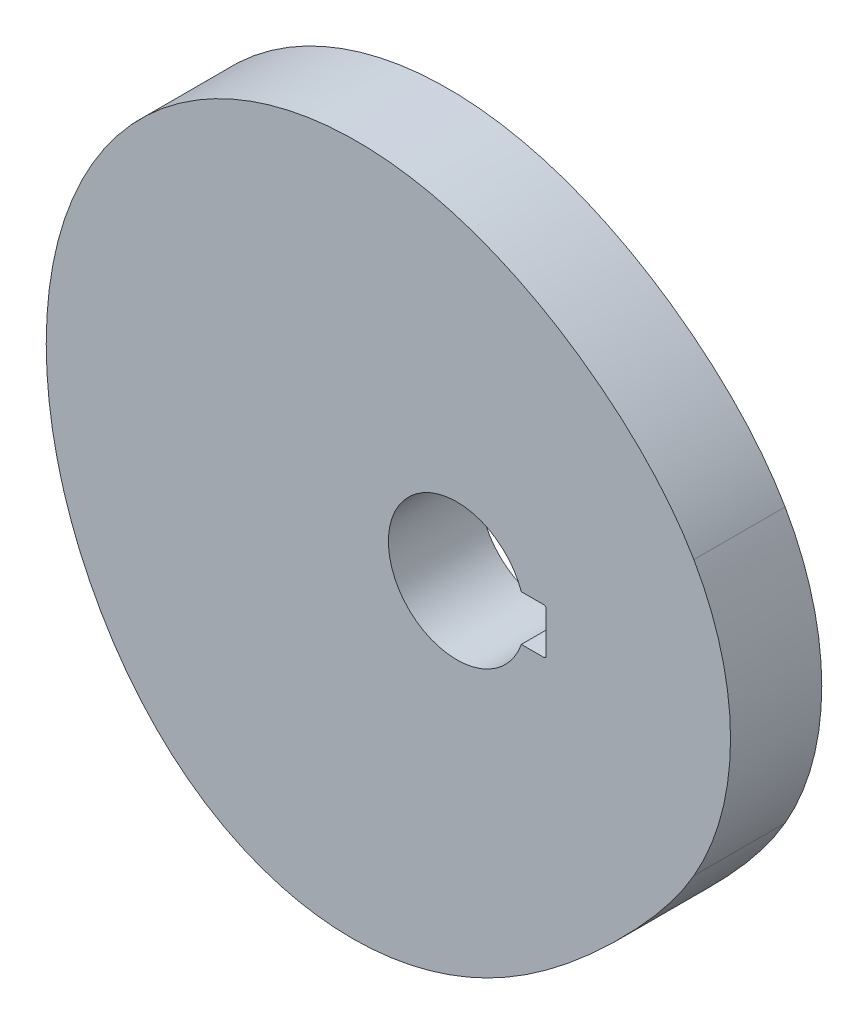
SolidWorks part; units mm, degrees
material "Plain Carbon Steel"
ref_plane "Front Plane" through (0, 0, 0) normal (0, 0, 1) x (1, 0, 0)
ref_plane "Top Plane" through (0, 0, 0) normal (0, 1, 0) x (1, 0, 0)
ref_plane "Right Plane" through (0, 0, 0) normal (1, 0, 0) x (0, 0, -1)
sketch "Displacement Sketch" plane through (0, 0, 0) normal (0, 0, 1) x (1, 0, 0)
  line L0 (0, 15) -> (0, 0) construction
  line L1 (0, 0) -> (47.1239, 0) construction
  line L2 (3.927, 0) -> (3.927, 15) construction
  line L3 (23.5619, 0) -> (23.5619, 15) construction
  line L4 (27.4889, 0) -> (27.4889, 15) construction
  line L5 (43.1969, 0) -> (43.1969, 15) construction
  line L6 (47.1239, 0) -> (47.1239, 15) construction
  line L7 (0, 0) -> (3.927, 0)
  line L8 (27.4889, 15) -> (23.5619, 15)
  line L9 (43.1969, 0) -> (47.1239, 0)
  spline S0 degree 4 poles (1.962, -0.0967) (2.0251, -0.0879) (2.1497, -0.0715) (2.3802, -0.0441) (2.7786, -0.0172) (3.1491, -0.0023) (3.8234, 0.0011) (4.1519, -0.0013) (4.7825, 0.0037) (5.2973, 0.0292) (5.8993, 0.0828) (6.4992, 0.198) (7.1843, 0.4092) (7.8229, 0.6945) (8.5028, 1.0958) (9.2434, 1.664) (10.1514, 2.5325) (11.1276, 3.6845) (12.1583, 5.0983) (13.2223, 6.6951) (14.2666, 8.3049) (15.3308, 9.9017) (16.361, 11.3155) (17.3382, 12.4675) (18.2447, 13.336) (18.9876, 13.9042) (19.6636, 14.3055) (20.2354, 14.5584) (20.6913, 14.7109) (21.0546, 14.8041) (21.3223, 14.8591) (21.5625, 14.8998) (21.7937, 14.9296) (22.0274, 14.9566) (22.3642, 14.9781) (22.6856, 14.9963) (23.3417, 15.0013) (23.6628, 14.9989) (24.3418, 15.0023) (24.7635, 15.0193) (25.1747, 15.049) (25.3985, 15.0791) (25.5259, 15.0967) knots 0 0 0 0 0 0.008159 0.016318 0.032637 0.048955 0.065274 0.0892 0.101163 0.113126 0.142767 0.163984 0.185201 0.206418 0.236195 0.268021 0.309045 0.372696 0.436348 0.5 0.563652 0.627304 0.690955 0.731979 0.763805 0.793582 0.814799 0.836016 0.846625 0.857233 0.864643 0.872053 0.879463 0.886874 0.898837 0.9108 0.934726 0.951045 0.967363 0.983682 1 1 1 1 1 construction
  spline S1 degree 4 poles (3.927, 0) (4.0838, 0) (4.3123, 0) (4.7825, 0.0037) (5.2973, 0.0292) (5.8993, 0.0828) (6.4992, 0.198) (7.1843, 0.4092) (7.8229, 0.6945) (8.5028, 1.0958) (9.2434, 1.664) (10.1514, 2.5325) (11.1276, 3.6845) (12.1583, 5.0983) (13.2223, 6.6951) (14.2666, 8.3049) (15.3308, 9.9017) (16.361, 11.3155) (17.3382, 12.4675) (18.2447, 13.336) (18.9876, 13.9042) (19.6636, 14.3055) (20.2354, 14.5584) (20.6913, 14.7109) (21.0546, 14.8041) (21.3223, 14.8591) (21.5625, 14.8998) (21.7937, 14.9296) (22.0274, 14.9566) (22.3642, 14.9781) (22.6856, 14.9963) (23.1748, 15) (23.4052, 15) (23.5619, 15) knots 0.065274 0.065274 0.065274 0.065274 0.065274 0.0892 0.101163 0.113126 0.142767 0.163984 0.185201 0.206418 0.236195 0.268021 0.309045 0.372696 0.436348 0.5 0.563652 0.627304 0.690955 0.731979 0.763805 0.793582 0.814799 0.836016 0.846625 0.857233 0.864643 0.872053 0.879463 0.886874 0.898837 0.9108 0.934726 0.934726 0.934726 0.934726 0.934726
  spline S2 degree 4 poles (25.917, 15.0967) (25.9672, 15.0879) (26.0664, 15.0716) (26.2503, 15.0442) (26.5692, 15.0173) (26.8684, 15.0023) (27.398, 14.9989) (27.6696, 15.0012) (28.1638, 14.9965) (28.4688, 14.9775) (28.7956, 14.949) (29.0691, 14.9044) (29.3652, 14.8416) (29.6303, 14.7623) (29.8895, 14.6683) (30.1363, 14.5572) (30.3781, 14.4298) (30.708, 14.2278) (31.1287, 13.9151) (31.7056, 13.3799) (32.4321, 12.5171) (33.1948, 11.3999) (33.9837, 10.0588) (34.759, 8.6207) (35.5133, 7.1717) (36.2737, 5.7258) (37.0683, 4.2981) (37.8437, 3.0586) (38.5964, 2.0494) (39.2866, 1.3197) (39.8479, 0.8516) (40.4053, 0.501) (40.8925, 0.2823) (41.3433, 0.149) (41.8164, 0.0573) (42.2412, 0.0166) (42.6103, 0.0017) (43.0977, -0.0005) (43.3551, 0.0006) (43.8251, -0.0023) (44.1115, -0.0173) (44.4386, -0.0442) (44.6184, -0.0716) (44.7185, -0.0879) (44.7693, -0.0967) knots 0 0 0 0 0 0.007472 0.014944 0.029888 0.044832 0.059777 0.081272 0.09202 0.102768 0.114604 0.126441 0.136767 0.147094 0.15742 0.167746 0.178072 0.188398 0.21612 0.247099 0.297177 0.359134 0.421092 0.48305 0.545008 0.606966 0.668924 0.730882 0.766656 0.797635 0.820922 0.841574 0.866069 0.878735 0.891402 0.915813 0.928018 0.940223 0.955168 0.970112 0.985056 0.992528 1 1 1 1 1 construction
  spline S3 degree 4 poles (27.4889, 15) (27.6137, 15) (27.7971, 15) (28.1638, 14.9965) (28.4688, 14.9775) (28.7956, 14.949) (29.0691, 14.9044) (29.3652, 14.8416) (29.6303, 14.7623) (29.8895, 14.6683) (30.1363, 14.5572) (30.3781, 14.4298) (30.708, 14.2278) (31.1287, 13.9151) (31.7056, 13.3799) (32.4321, 12.5171) (33.1948, 11.3999) (33.9837, 10.0588) (34.759, 8.6207) (35.5133, 7.1717) (36.2737, 5.7258) (37.0683, 4.2981) (37.8437, 3.0586) (38.5964, 2.0494) (39.2866, 1.3197) (39.8479, 0.8516) (40.4053, 0.501) (40.8925, 0.2823) (41.3433, 0.149) (41.8164, 0.0573) (42.2412, 0.0166) (42.6103, 0.0017) (42.9834, 0) (43.1261, 0) (43.1969, 0) knots 0.059777 0.059777 0.059777 0.059777 0.059777 0.081272 0.09202 0.102768 0.114604 0.126441 0.136767 0.147094 0.15742 0.167746 0.178072 0.188398 0.21612 0.247099 0.297177 0.359134 0.421092 0.48305 0.545008 0.606966 0.668924 0.730882 0.766656 0.797635 0.820922 0.841574 0.866069 0.878735 0.891402 0.915813 0.928018 0.940223 0.940223 0.940223 0.940223 0.940223
  point P2 (0, 0)
  point P17 (0, 0)
  dimension "D1" = 15
  dimension "D2" = 47.1239
  dimension "D3" = 3.927
  dimension "D4" = 19.635
  dimension "D5" = 3.927
  dimension "D6" = 15.708
  dimension "D7" = 3.927
sketch "Velocity Sketch" plane through (0, 0, 0) normal (0, 0, 1) x (1, 0, 0)
  line L0 (0, -15) -> (0, -65) construction
  line L1 (0, -40) -> (47.1239, -40) construction
  line L2 (3.927, -15) -> (3.927, -65) construction
  line L3 (23.5619, -15) -> (23.5619, -65) construction
  line L4 (27.4889, -15) -> (27.4889, -65) construction
  line L5 (43.1969, -15) -> (43.1969, -65) construction
  line L6 (47.1239, -15) -> (47.1239, -65) construction
  line L7 (0, -40) -> (3.927, -40)
  line L8 (23.5619, -40) -> (27.4889, -40)
  line L9 (43.1969, -40) -> (47.1239, -40)
  spline S0 degree 4 poles (1.9635, -38.9057) (2.0257, -38.9728) (2.1526, -39.1046) (2.3179, -39.263) (2.5282, -39.4396) (2.7124, -39.5752) (2.8656, -39.6755) (3.0312, -39.7696) (3.21, -39.8541) (3.378, -39.9155) (3.5323, -39.9566) (3.6606, -39.9808) (3.7704, -39.9939) (3.8976, -40.0012) (3.9765, -40.0003) (4.0914, -39.9931) (4.2047, -39.9788) (4.3113, -39.9585) (4.4273, -39.9287) (4.5497, -39.8882) (4.6855, -39.8341) (4.8338, -39.7637) (5.0005, -39.6692) (5.2228, -39.5203) (5.4703, -39.3234) (5.7369, -39.0742) (6.0182, -38.7713) (6.2635, -38.4767) (6.4789, -38.1966) (6.7119, -37.8755) (6.9601, -37.5119) (7.2378, -37.08) (7.6188, -36.4531) (8.0578, -35.69) (8.695, -34.5334) (9.3923, -33.2428) (10.1106, -31.9631) (10.8521, -30.798) (11.4447, -29.9912) (12.0701, -29.306) (12.6823, -28.8165) (13.3594, -28.5265) (13.9982, -28.5224) (14.4931, -28.6816) (14.9938, -28.9673) (15.4821, -29.3759) (16.0352, -29.9801) (16.6301, -30.7877) (17.3726, -31.9534) (18.0917, -33.2337) (18.7893, -34.5249) (19.4267, -35.6821) (19.8657, -36.4456) (20.2468, -37.073) (20.5641, -37.567) (20.8732, -38.0148) (21.1744, -38.4151) (21.4671, -38.7672) (21.7491, -39.0713) (22.0564, -39.3589) (22.3514, -39.5861) (22.6045, -39.7396) (22.8026, -39.8338) (22.9386, -39.888) (23.0611, -39.9286) (23.1771, -39.9584) (23.2842, -39.9788) (23.3789, -39.9907) (23.4581, -39.9971) (23.5401, -40.0006) (23.6106, -40) (23.7191, -39.9939) (23.8283, -39.9808) (23.9566, -39.9566) (24.111, -39.9155) (24.322, -39.8383) (24.5805, -39.7075) (24.8544, -39.5266) (25.138, -39.2946) (25.3363, -39.1046) (25.4632, -38.9728) (25.5254, -38.9057) knots 0 0 0 0 0 0.010194 0.020387 0.025484 0.030581 0.035677 0.040774 0.046689 0.052603 0.05556 0.058517 0.061474 0.064432 0.068544 0.0706 0.072656 0.076768 0.08088 0.083926 0.086973 0.093066 0.099159 0.105252 0.116762 0.128271 0.13978 0.15129 0.159464 0.167638 0.183987 0.200336 0.216684 0.249382 0.282079 0.347474 0.380171 0.412868 0.435887 0.458906 0.483278 0.499726 0.516191 0.528398 0.540605 0.563699 0.586794 0.619507 0.652221 0.717647 0.750361 0.783074 0.799431 0.815787 0.832144 0.8485 0.860048 0.871595 0.883143 0.89469 0.906897 0.913 0.916052 0.919104 0.92322 0.927336 0.929394 0.931452 0.93351 0.935568 0.938526 0.941483 0.94444 0.947397 0.953311 0.959226 0.969419 0.979613 0.989806 1 1 1 1 1 construction
  spline S1 degree 4 poles (3.927, -40) (3.9591, -40) (4.0069, -39.9984) (4.0914, -39.9931) (4.2047, -39.9788) (4.3113, -39.9585) (4.4273, -39.9287) (4.5497, -39.8882) (4.6855, -39.8341) (4.8338, -39.7637) (5.0005, -39.6692) (5.2228, -39.5203) (5.4703, -39.3234) (5.7369, -39.0742) (6.0182, -38.7713) (6.2635, -38.4767) (6.4789, -38.1966) (6.7119, -37.8755) (6.9601, -37.5119) (7.2378, -37.08) (7.6188, -36.4531) (8.0578, -35.69) (8.695, -34.5334) (9.3923, -33.2428) (10.1106, -31.9631) (10.8521, -30.798) (11.4447, -29.9912) (12.0701, -29.306) (12.6823, -28.8165) (13.3594, -28.5265) (13.9982, -28.5224) (14.4931, -28.6816) (14.9938, -28.9673) (15.4821, -29.3759) (16.0352, -29.9801) (16.6301, -30.7877) (17.3726, -31.9534) (18.0917, -33.2337) (18.7893, -34.5249) (19.4267, -35.6821) (19.8657, -36.4456) (20.2468, -37.073) (20.5641, -37.567) (20.8732, -38.0148) (21.1744, -38.4151) (21.4671, -38.7672) (21.7491, -39.0713) (22.0564, -39.3589) (22.3514, -39.5861) (22.6045, -39.7396) (22.8026, -39.8338) (22.9386, -39.888) (23.0611, -39.9286) (23.1771, -39.9584) (23.2842, -39.9788) (23.3789, -39.9907) (23.4581, -39.9971) (23.5136, -39.9995) (23.5459, -40) (23.5619, -40) knots 0.064432 0.064432 0.064432 0.064432 0.064432 0.068544 0.0706 0.072656 0.076768 0.08088 0.083926 0.086973 0.093066 0.099159 0.105252 0.116762 0.128271 0.13978 0.15129 0.159464 0.167638 0.183987 0.200336 0.216684 0.249382 0.282079 0.347474 0.380171 0.412868 0.435887 0.458906 0.483278 0.499726 0.516191 0.528398 0.540605 0.563699 0.586794 0.619507 0.652221 0.717647 0.750361 0.783074 0.799431 0.815787 0.832144 0.8485 0.860048 0.871595 0.883143 0.89469 0.906897 0.913 0.916052 0.919104 0.92322 0.927336 0.929394 0.931452 0.93351 0.935568 0.935568 0.935568 0.935568 0.935568
  spline S2 degree 4 poles (25.9181, -41.3678) (25.969, -41.2822) (26.0474, -41.155) (26.1567, -40.9884) (26.3034, -40.7872) (26.428, -40.6317) (26.5612, -40.4834) (26.7044, -40.3447) (26.8491, -40.2282) (26.9938, -40.1353) (27.1202, -40.0746) (27.2225, -40.0387) (27.3087, -40.0172) (27.3821, -40.0055) (27.4558, -39.9999) (27.5062, -39.9994) (27.5651, -40.003) (27.6216, -40.0095) (27.6752, -40.0191) (27.7266, -40.0316) (27.79, -40.0509) (27.8853, -40.0869) (28.0075, -40.1485) (28.1907, -40.2707) (28.3839, -40.4445) (28.5692, -40.6505) (28.7482, -40.8845) (28.8972, -41.1024) (29.0371, -41.3263) (29.1693, -41.5547) (29.3267, -41.8447) (29.5183, -42.2252) (29.738, -42.6988) (29.9816, -43.2668) (30.2236, -43.8681) (30.5135, -44.6245) (30.8469, -45.5378) (31.2234, -46.6076) (31.6487, -47.832) (32.0801, -49.0542) (32.4735, -50.118) (32.8326, -51.0215) (33.142, -51.7326) (33.3888, -52.2556) (33.6408, -52.7378) (33.8982, -53.1762) (34.223, -53.6432) (34.5556, -54.0066) (34.9078, -54.2495) (35.2458, -54.3293) (35.458, -54.327) (35.7081, -54.2632) (35.9731, -54.1157) (36.2611, -53.8668) (36.5554, -53.5158) (36.8301, -53.1086) (37.0915, -52.6536) (37.3438, -52.1599) (37.5898, -51.63) (37.8954, -50.918) (38.2495, -50.0196) (38.6386, -48.9625) (39.0662, -47.7483) (39.4887, -46.5322) (39.8632, -45.4699) (40.1952, -44.5632) (40.4842, -43.8123) (40.7255, -43.2156) (40.9683, -42.653) (41.187, -42.1848) (41.3776, -41.8095) (41.5335, -41.5246) (41.6646, -41.3002) (41.8032, -41.0803) (41.9509, -40.8664) (42.1281, -40.6369) (42.3115, -40.4352) (42.5023, -40.2652) (42.6833, -40.1457) (42.8038, -40.0854) (42.8984, -40.0501) (42.9739, -40.0273) (43.0476, -40.0102) (43.1489, -40) (43.2166, -39.9988) (43.3032, -40.0055) (43.3772, -40.0172) (43.4633, -40.0387) (43.5656, -40.0746) (43.6921, -40.1353) (43.8367, -40.2282) (43.9814, -40.3447) (44.1247, -40.4834) (44.2578, -40.6317) (44.3824, -40.7872) (44.5292, -40.9884) (44.6384, -41.155) (44.7169, -41.2822) (44.7677, -41.3678) knots 0 0 0 0 0 0.010463 0.015694 0.020925 0.026157 0.031388 0.03662 0.041851 0.045635 0.049419 0.051311 0.053203 0.055095 0.056987 0.058388 0.05979 0.061191 0.062592 0.063993 0.065395 0.068197 0.073266 0.078335 0.088472 0.095404 0.102336 0.109267 0.116199 0.123131 0.130063 0.143926 0.160948 0.17797 0.194992 0.212014 0.246057 0.280101 0.314145 0.348188 0.382232 0.399254 0.416276 0.429638 0.443 0.456362 0.469724 0.489196 0.494701 0.500206 0.505766 0.511326 0.521544 0.531762 0.545538 0.559313 0.573088 0.586864 0.60377 0.620676 0.654487 0.688299 0.722111 0.755922 0.789734 0.80664 0.823546 0.840451 0.857357 0.871007 0.877832 0.884657 0.891482 0.898307 0.905132 0.911957 0.921925 0.926909 0.931893 0.934673 0.936063 0.937453 0.940233 0.943013 0.944905 0.946797 0.948689 0.950581 0.954365 0.958149 0.96338 0.968612 0.973843 0.979075 0.984306 0.989537 1 1 1 1 1 construction
  spline S3 degree 4 poles (27.4889, -40) (27.5008, -40) (27.5245, -40.0005) (27.5651, -40.003) (27.6216, -40.0095) (27.6752, -40.0191) (27.7266, -40.0316) (27.79, -40.0509) (27.8853, -40.0869) (28.0075, -40.1485) (28.1907, -40.2707) (28.3839, -40.4445) (28.5692, -40.6505) (28.7482, -40.8845) (28.8972, -41.1024) (29.0371, -41.3263) (29.1693, -41.5547) (29.3267, -41.8447) (29.5183, -42.2252) (29.738, -42.6988) (29.9816, -43.2668) (30.2236, -43.8681) (30.5135, -44.6245) (30.8469, -45.5378) (31.2234, -46.6076) (31.6487, -47.832) (32.0801, -49.0542) (32.4735, -50.118) (32.8326, -51.0215) (33.142, -51.7326) (33.3888, -52.2556) (33.6408, -52.7378) (33.8982, -53.1762) (34.223, -53.6432) (34.5556, -54.0066) (34.9078, -54.2495) (35.2458, -54.3293) (35.458, -54.327) (35.7081, -54.2632) (35.9731, -54.1157) (36.2611, -53.8668) (36.5554, -53.5158) (36.8301, -53.1086) (37.0915, -52.6536) (37.3438, -52.1599) (37.5898, -51.63) (37.8954, -50.918) (38.2495, -50.0196) (38.6386, -48.9625) (39.0662, -47.7483) (39.4887, -46.5322) (39.8632, -45.4699) (40.1952, -44.5632) (40.4842, -43.8123) (40.7255, -43.2156) (40.9683, -42.653) (41.187, -42.1848) (41.3776, -41.8095) (41.5335, -41.5246) (41.6646, -41.3002) (41.8032, -41.0803) (41.9509, -40.8664) (42.1281, -40.6369) (42.3115, -40.4352) (42.5023, -40.2652) (42.6833, -40.1457) (42.8038, -40.0854) (42.8984, -40.0501) (42.9739, -40.0273) (43.0476, -40.0102) (43.1272, -40.0021) (43.1735, -40) (43.1969, -40) knots 0.056987 0.056987 0.056987 0.056987 0.056987 0.058388 0.05979 0.061191 0.062592 0.063993 0.065395 0.068197 0.073266 0.078335 0.088472 0.095404 0.102336 0.109267 0.116199 0.123131 0.130063 0.143926 0.160948 0.17797 0.194992 0.212014 0.246057 0.280101 0.314145 0.348188 0.382232 0.399254 0.416276 0.429638 0.443 0.456362 0.469724 0.489196 0.494701 0.500206 0.505766 0.511326 0.521544 0.531762 0.545538 0.559313 0.573088 0.586864 0.60377 0.620676 0.654487 0.688299 0.722111 0.755922 0.789734 0.80664 0.823546 0.840451 0.857357 0.871007 0.877832 0.884657 0.891482 0.898307 0.905132 0.911957 0.921925 0.926909 0.931893 0.934673 0.936063 0.937453 0.940233 0.943013 0.943013 0.943013 0.943013 0.943013
  point P15 (23.5619, -40)
  point P27 (43.1969, -40)
  point P28 (3.927, -40)
  point P35 (27.4889, -40)
  dimension "D1" = 50
  dimension "D2" = 15
  dimension "D3" = 47.1239
sketch "Acceleration Sketch" plane through (0, 0, 0) normal (0, 0, 1) x (1, 0, 0)
  line L0 (0, -80) -> (0, -130) construction
  line L1 (0, -15) -> (0, -65) construction
  line L2 (3.927, -80) -> (3.927, -130) construction
  line L3 (23.5619, -80) -> (23.5619, -130) construction
  line L4 (27.4889, -80) -> (27.4889, -130) construction
  line L5 (43.1969, -80) -> (43.1969, -130) construction
  line L6 (47.1239, -80) -> (47.1239, -130) construction
  line L7 (0, -105) -> (47.1239, -105) construction
  spline S0 degree 4 poles (2.572, -110.7775) (2.5826, -110.7352) (2.6049, -110.6462) (2.6568, -110.4348) (2.7247, -110.1667) (2.8631, -109.5866) (2.9168, -109.376) (3.1103, -108.5487) (3.2451, -107.9915) (3.7647, -105.7173) (3.9235, -105.0128) (4.4418, -102.7383) (4.726, -101.5165) (5.0905, -99.9824) (5.4257, -98.6411) (5.7628, -97.3573) (6.0541, -96.3347) (6.324, -95.4451) (6.5477, -94.7627) (6.7807, -94.1024) (7.0182, -93.4965) (7.2387, -92.994) (7.4321, -92.6044) (7.6103, -92.2868) (7.7652, -92.0405) (7.9385, -91.8029) (8.1364, -91.5783) (8.3751, -91.3792) (8.6628, -91.239) (9.0399, -91.2355) (9.3821, -91.4294) (9.658, -91.7026) (9.9031, -92.031) (10.1006, -92.3508) (10.3757, -92.8619) (10.6941, -93.5774) (11.0415, -94.5007) (11.4096, -95.6315) (11.7539, -96.8019) (12.0819, -98.0088) (12.4807, -99.5681) (12.9408, -101.482) (13.4552, -103.72) (14.0337, -106.28) (14.5481, -108.518) (15.0082, -110.4319) (15.4071, -111.9912) (15.735, -113.1981) (16.0793, -114.3685) (16.4474, -115.4993) (16.7948, -116.4226) (17.1133, -117.1381) (17.3883, -117.6492) (17.5858, -117.969) (17.831, -118.2974) (18.1068, -118.5706) (18.449, -118.7645) (18.8261, -118.761) (19.1138, -118.6208) (19.3525, -118.4218) (19.5505, -118.197) (19.7664, -117.9009) (19.991, -117.5251) (20.221, -117.0728) (20.4706, -116.5036) (20.7083, -115.8976) (20.9412, -115.2374) (21.1649, -114.5549) (21.4349, -113.6653) (21.7261, -112.6427) (22.0633, -111.3589) (22.3985, -110.0176) (22.763, -108.4835) (23.0471, -107.2617) (23.5654, -104.9872) (23.7242, -104.2827) (24.2438, -102.0085) (24.3787, -101.4513) (24.5722, -100.624) (24.6258, -100.4134) (24.7642, -99.8333) (24.8321, -99.5652) (24.884, -99.3538) (24.9063, -99.2648) (24.917, -99.2225) knots 0 0 0 0 0 0.002588 0.005177 0.010354 0.020707 0.025884 0.031061 0.041414 0.082829 0.103192 0.123556 0.14392 0.164284 0.184648 0.205012 0.215194 0.225376 0.235558 0.24574 0.253858 0.261975 0.266034 0.270093 0.274152 0.278211 0.282468 0.286725 0.291483 0.295696 0.302677 0.307932 0.313188 0.318443 0.323699 0.340297 0.356895 0.373493 0.390091 0.408409 0.426727 0.463364 0.5 0.536636 0.573273 0.591591 0.609909 0.626507 0.643105 0.659703 0.676301 0.681557 0.686812 0.692068 0.697323 0.704304 0.708517 0.713275 0.717532 0.721789 0.725848 0.729907 0.738025 0.746142 0.75426 0.764442 0.774624 0.784806 0.794988 0.815352 0.835716 0.85608 0.876444 0.896808 0.917171 0.958586 0.968939 0.974116 0.979293 0.989646 0.994823 0.997412 1 1 1 1 1 construction
  spline S1 degree 4 poles (3.927, -105) (3.9944, -104.7033) (4.1329, -104.0938) (4.4418, -102.7383) (4.726, -101.5165) (5.0905, -99.9824) (5.4257, -98.6411) (5.7628, -97.3573) (6.0541, -96.3347) (6.324, -95.4451) (6.5477, -94.7627) (6.7807, -94.1024) (7.0182, -93.4965) (7.2387, -92.994) (7.4321, -92.6044) (7.6103, -92.2868) (7.7652, -92.0405) (7.9385, -91.8029) (8.1364, -91.5783) (8.3751, -91.3792) (8.6628, -91.239) (9.0399, -91.2355) (9.3821, -91.4294) (9.658, -91.7026) (9.9031, -92.031) (10.1006, -92.3508) (10.3757, -92.8619) (10.6941, -93.5774) (11.0415, -94.5007) (11.4096, -95.6315) (11.7539, -96.8019) (12.0819, -98.0088) (12.4807, -99.5681) (12.9408, -101.482) (13.4552, -103.72) (14.0337, -106.28) (14.5481, -108.518) (15.0082, -110.4319) (15.4071, -111.9912) (15.735, -113.1981) (16.0793, -114.3685) (16.4474, -115.4993) (16.7948, -116.4226) (17.1133, -117.1381) (17.3883, -117.6492) (17.5858, -117.969) (17.831, -118.2974) (18.1068, -118.5706) (18.449, -118.7645) (18.8261, -118.761) (19.1138, -118.6208) (19.3525, -118.4218) (19.5505, -118.197) (19.7664, -117.9009) (19.991, -117.5251) (20.221, -117.0728) (20.4706, -116.5036) (20.7083, -115.8976) (20.9412, -115.2374) (21.1649, -114.5549) (21.4349, -113.6653) (21.7261, -112.6427) (22.0633, -111.3589) (22.3985, -110.0176) (22.763, -108.4835) (23.0471, -107.2617) (23.356, -105.9062) (23.4945, -105.2967) (23.5619, -105) knots 0.082829 0.082829 0.082829 0.082829 0.082829 0.103192 0.123556 0.14392 0.164284 0.184648 0.205012 0.215194 0.225376 0.235558 0.24574 0.253858 0.261975 0.266034 0.270093 0.274152 0.278211 0.282468 0.286725 0.291483 0.295696 0.302677 0.307932 0.313188 0.318443 0.323699 0.340297 0.356895 0.373493 0.390091 0.408409 0.426727 0.463364 0.5 0.536636 0.573273 0.591591 0.609909 0.626507 0.643105 0.659703 0.676301 0.681557 0.686812 0.692068 0.697323 0.704304 0.708517 0.713275 0.717532 0.721789 0.725848 0.729907 0.738025 0.746142 0.75426 0.764442 0.774624 0.784806 0.794988 0.815352 0.835716 0.85608 0.876444 0.896808 0.917171 0.917171 0.917171 0.917171 0.917171
  spline S2 degree 4 poles (26.4484, -96.3102) (26.5118, -96.8222) (26.5658, -97.2281) (26.8032, -99.1812) (26.9742, -100.5869) (27.3892, -104.1392) (27.5686, -105.6882) (27.9878, -109.2775) (28.2426, -111.3928) (28.6075, -114.3425) (28.9332, -116.7713) (29.3318, -119.5372) (29.6889, -121.6296) (30.0509, -123.449) (30.3524, -124.5941) (30.5472, -125.2296) (30.7103, -125.6432) (30.821, -125.8896) (30.926, -126.0792) (31.0123, -126.2131) (31.0985, -126.3183) (31.1798, -126.3936) (31.2441, -126.4375) (31.2991, -126.4643) (31.3487, -126.4798) (31.3966, -126.4868) (31.4431, -126.4862) (31.491, -126.4779) (31.541, -126.4609) (31.5967, -126.4322) (31.6626, -126.3849) (31.7478, -126.3032) (31.8681, -126.1482) (32.0585, -125.8141) (32.3727, -125.0186) (32.7489, -123.6119) (33.1471, -121.6395) (33.5462, -119.2173) (33.9186, -116.6385) (34.2594, -114.0551) (34.5809, -111.4694) (34.8901, -108.8821) (35.1927, -106.2941) (35.4931, -103.7059) (35.7957, -101.1179) (36.1049, -98.5306) (36.4264, -95.9449) (36.7673, -93.3615) (37.1397, -90.7827) (37.5387, -88.3605) (37.9369, -86.3881) (38.3131, -84.9814) (38.6274, -84.1859) (38.8178, -83.8518) (38.9381, -83.6968) (39.0232, -83.6151) (39.0891, -83.5678) (39.1448, -83.5391) (39.1948, -83.5221) (39.2428, -83.5138) (39.2893, -83.5132) (39.3371, -83.5202) (39.3867, -83.5357) (39.4417, -83.5624) (39.506, -83.6068) (39.5872, -83.6808) (39.7, -83.8211) (39.8275, -84.031) (39.9606, -84.3179) (40.1387, -84.7711) (40.3334, -85.4056) (40.635, -86.5512) (40.9969, -88.3703) (41.354, -90.4629) (41.7526, -93.2287) (42.0783, -95.6575) (42.4432, -98.6072) (42.6981, -100.7225) (43.1172, -104.3118) (43.2966, -105.8608) (43.7116, -109.4131) (43.8826, -110.8188) (44.12, -112.7719) (44.174, -113.1778) (44.2375, -113.6898) knots 0 0 0 0 0 0.013744 0.027488 0.054976 0.082464 0.107561 0.132658 0.157755 0.182852 0.207948 0.233045 0.258142 0.266928 0.275713 0.279145 0.282576 0.284145 0.285714 0.287455 0.28853 0.289309 0.289879 0.290393 0.290836 0.291269 0.291702 0.292145 0.29267 0.293258 0.294064 0.295205 0.297118 0.300661 0.308565 0.327485 0.35213 0.376775 0.40142 0.426065 0.45071 0.475355 0.5 0.524645 0.54929 0.573935 0.59858 0.623225 0.64787 0.672515 0.691435 0.699339 0.702882 0.704795 0.705936 0.706742 0.70733 0.707855 0.708298 0.708731 0.709164 0.709607 0.710121 0.710691 0.71147 0.712545 0.714286 0.717424 0.720855 0.724287 0.733072 0.741858 0.766955 0.792052 0.817148 0.842245 0.867342 0.892439 0.917536 0.945024 0.972512 0.986256 1 1 1 1 1 construction
  spline S3 degree 4 poles (27.4889, -105) (27.553, -105.5502) (27.6807, -106.6482) (27.9878, -109.2775) (28.2426, -111.3928) (28.6075, -114.3425) (28.9332, -116.7713) (29.3318, -119.5372) (29.6889, -121.6296) (30.0509, -123.449) (30.3524, -124.5941) (30.5472, -125.2296) (30.7103, -125.6432) (30.821, -125.8896) (30.926, -126.0792) (31.0123, -126.2131) (31.0985, -126.3183) (31.1798, -126.3936) (31.2441, -126.4375) (31.2991, -126.4643) (31.3487, -126.4798) (31.3966, -126.4868) (31.4431, -126.4862) (31.491, -126.4779) (31.541, -126.4609) (31.5967, -126.4322) (31.6626, -126.3849) (31.7478, -126.3032) (31.8681, -126.1482) (32.0585, -125.8141) (32.3727, -125.0186) (32.7489, -123.6119) (33.1471, -121.6395) (33.5462, -119.2173) (33.9186, -116.6385) (34.2594, -114.0551) (34.5809, -111.4694) (34.8901, -108.8821) (35.1927, -106.2941) (35.4931, -103.7059) (35.7957, -101.1179) (36.1049, -98.5306) (36.4264, -95.9449) (36.7673, -93.3615) (37.1397, -90.7827) (37.5387, -88.3605) (37.9369, -86.3881) (38.3131, -84.9814) (38.6274, -84.1859) (38.8178, -83.8518) (38.9381, -83.6968) (39.0232, -83.6151) (39.0891, -83.5678) (39.1448, -83.5391) (39.1948, -83.5221) (39.2428, -83.5138) (39.2893, -83.5132) (39.3371, -83.5202) (39.3867, -83.5357) (39.4417, -83.5624) (39.506, -83.6068) (39.5872, -83.6808) (39.7, -83.8211) (39.8275, -84.031) (39.9606, -84.3179) (40.1387, -84.7711) (40.3334, -85.4056) (40.635, -86.5512) (40.9969, -88.3703) (41.354, -90.4629) (41.7526, -93.2287) (42.0783, -95.6575) (42.4432, -98.6072) (42.6981, -100.7225) (43.0051, -103.3518) (43.1329, -104.4498) (43.1969, -105) knots 0.082464 0.082464 0.082464 0.082464 0.082464 0.107561 0.132658 0.157755 0.182852 0.207948 0.233045 0.258142 0.266928 0.275713 0.279145 0.282576 0.284145 0.285714 0.287455 0.28853 0.289309 0.289879 0.290393 0.290836 0.291269 0.291702 0.292145 0.29267 0.293258 0.294064 0.295205 0.297118 0.300661 0.308565 0.327485 0.35213 0.376775 0.40142 0.426065 0.45071 0.475355 0.5 0.524645 0.54929 0.573935 0.59858 0.623225 0.64787 0.672515 0.691435 0.699339 0.702882 0.704795 0.705936 0.706742 0.70733 0.707855 0.708298 0.708731 0.709164 0.709607 0.710121 0.710691 0.71147 0.712545 0.714286 0.717424 0.720855 0.724287 0.733072 0.741858 0.766955 0.792052 0.817148 0.842245 0.867342 0.892439 0.917536 0.917536 0.917536 0.917536 0.917536
  point P18 (23.8027, -105)
  point P26 (0, 0)
  point P30 (3.927, -105)
  point P31 (22.5917, -105)
  point P32 (0, 0)
  point P33 (0, 0)
  point P34 (0, 0)
  point P35 (0, 0)
  point P38 (96.3313, -100.333)
  point P40 (0, 0)
  point P41 (0, 0)
  point P42 (81.6814, -111.0248)
  point P43 (0, 0)
  point P44 (0, 0)
  point P45 (0, 0)
  point P46 (81.6814, -109.963)
  point P47 (81.6814, -105)
  point P48 (60.6009, -105)
  point P49 (0, 0)
  point P50 (0, 0)
  dimension "D1" = 15
sketch "Cam Profile Sketch" plane through (0, 0, 0) normal (0, 0, 1) x (1, 0, 0)
  line L0 (-50, 0) -> (-95, 0) construction
  line L1 (-50, 0) -> (-24.0192, 15) construction
  line L3 (-50, 0) -> (-88.9711, -22.5) construction
  line L4 (-24.0192, -15) -> (-50, 0) construction
  circle A1 centre (-50, 0) radius 30 construction
  arc A2 (-95, 0) -> (-88.9711, -22.5) centre (-50, 0) ccw
  arc A3 (-24.0192, -15) -> (-24.0192, 15) centre (-50, 0) ccw
  spline S0 degree 4 poles (-21.1156, 7.7394) (-21.1709, 7.9804) (-21.2882, 8.4609) (-21.4832, 9.1753) (-21.7832, 10.1194) (-22.1164, 11.0434) (-22.4869, 11.9572) (-22.8822, 12.8417) (-23.2666, 13.6216) (-23.5877, 14.234) (-23.9319, 14.8498) (-24.0959, 15.1341) (-24.3727, 15.5992) (-24.6187, 15.9971) (-24.8637, 16.3797) (-25.1191, 16.767) (-25.3798, 17.1502) (-25.6453, 17.5288) (-25.9456, 17.9449) (-26.2825, 18.3967) (-26.6579, 18.8827) (-27.0737, 19.4011) (-27.6051, 20.0396) (-28.2603, 20.7909) (-29.1374, 21.7417) (-30.2569, 22.8711) (-31.5134, 24.0468) (-32.9135, 25.258) (-34.7029, 26.6937) (-36.9167, 28.3043) (-39.5923, 30.0263) (-42.7706, 31.7702) (-46.0705, 33.2727) (-49.4807, 34.5058) (-53.1511, 35.4849) (-56.9011, 36.1019) (-60.6955, 36.3289) (-64.4915, 36.1457) (-68.0781, 35.5924) (-71.585, 34.6579) (-74.9693, 33.3466) (-78.1887, 31.6704) (-81.2166, 29.6392) (-84.013, 27.2738) (-86.224, 24.9368) (-88.2202, 22.3966) (-89.7284, 20.0743) (-90.8451, 18.055) (-91.8191, 15.9648) (-92.4856, 14.3205) (-92.9853, 12.8974) (-93.3529, 11.7109) (-93.6163, 10.7709) (-93.8117, 10.0146) (-94.0369, 9.0649) (-94.244, 8.0743) (-94.4303, 7.0448) (-94.5929, 5.974) (-94.711, 5.0612) (-94.8088, 4.1412) (-94.8865, 3.2281) (-94.9443, 2.2977) (-94.9778, 1.5066) (-94.9945, 0.8074) (-95.0008, 0.1224) (-95.0002, -0.2509) (-94.9921, -0.9704) (-94.9749, -1.5533) (-94.9493, -2.1851) (-94.9154, -2.8074) (-94.8732, -3.4304) (-94.8229, -4.0525) (-94.7499, -4.8295) (-94.6463, -5.7602) (-94.5028, -6.8433) (-94.3325, -7.9225) (-94.1679, -8.8444) (-94.0484, -9.4571) (-93.9863, -9.763) (-93.9547, -9.9158) knots 0 0 0 0 0 0.008397 0.016795 0.025192 0.033589 0.04186 0.050132 0.058403 0.062538 0.066674 0.070604 0.074535 0.078465 0.082396 0.086326 0.090257 0.094188 0.098118 0.103763 0.109408 0.115053 0.120698 0.131988 0.143278 0.159 0.174722 0.190444 0.206166 0.236936 0.267706 0.298477 0.329247 0.360017 0.390787 0.427383 0.458153 0.488923 0.519694 0.550464 0.581234 0.612004 0.642774 0.674103 0.705433 0.721097 0.752426 0.768091 0.783756 0.79942 0.812689 0.819323 0.825957 0.832591 0.839225 0.852494 0.860326 0.868158 0.875991 0.883823 0.891655 0.899488 0.90732 0.911236 0.915152 0.920455 0.925758 0.931061 0.936364 0.941667 0.94697 0.952273 0.957576 0.968182 0.978788 0.989394 0.994697 1 1 1 1 1 construction
  spline S1 degree 4 poles (-24.0192, 15) (-24.0683, 15.085) (-24.1678, 15.2549) (-24.3727, 15.5992) (-24.6187, 15.9971) (-24.8637, 16.3797) (-25.1191, 16.767) (-25.3798, 17.1502) (-25.6453, 17.5288) (-25.9456, 17.9449) (-26.2825, 18.3967) (-26.6579, 18.8827) (-27.0737, 19.4011) (-27.6051, 20.0396) (-28.2603, 20.7909) (-29.1374, 21.7417) (-30.2569, 22.8711) (-31.5134, 24.0468) (-32.9135, 25.258) (-34.7029, 26.6937) (-36.9167, 28.3043) (-39.5923, 30.0263) (-42.7706, 31.7702) (-46.0705, 33.2727) (-49.4807, 34.5058) (-53.1511, 35.4849) (-56.9011, 36.1019) (-60.6955, 36.3289) (-64.4915, 36.1457) (-68.0781, 35.5924) (-71.585, 34.6579) (-74.9693, 33.3466) (-78.1887, 31.6704) (-81.2166, 29.6392) (-84.013, 27.2738) (-86.224, 24.9368) (-88.2202, 22.3966) (-89.7284, 20.0743) (-90.8451, 18.055) (-91.8191, 15.9648) (-92.4856, 14.3205) (-92.9853, 12.8974) (-93.3529, 11.7109) (-93.6163, 10.7709) (-93.8117, 10.0146) (-94.0369, 9.0649) (-94.244, 8.0743) (-94.4303, 7.0448) (-94.5929, 5.974) (-94.711, 5.0612) (-94.8088, 4.1412) (-94.8865, 3.2281) (-94.9443, 2.2977) (-94.9778, 1.5066) (-94.9945, 0.8074) (-94.9992, 0.2957) (-95, 0.0978) (-95, 0) knots 0.066674 0.066674 0.066674 0.066674 0.066674 0.070604 0.074535 0.078465 0.082396 0.086326 0.090257 0.094188 0.098118 0.103763 0.109408 0.115053 0.120698 0.131988 0.143278 0.159 0.174722 0.190444 0.206166 0.236936 0.267706 0.298477 0.329247 0.360017 0.390787 0.427383 0.458153 0.488923 0.519694 0.550464 0.581234 0.612004 0.642774 0.674103 0.705433 0.721097 0.752426 0.768091 0.783756 0.79942 0.812689 0.819323 0.825957 0.832591 0.839225 0.852494 0.860326 0.868158 0.875991 0.883823 0.891655 0.899488 0.90732 0.911236 0.915152 0.915152 0.915152 0.915152 0.915152
  spline S2 degree 4 poles (-21.5603, -9.2406) (-21.6128, -9.4313) (-21.7224, -9.8112) (-21.901, -10.377) (-22.1657, -11.1224) (-22.4548, -11.8555) (-22.7279, -12.4868) (-22.9749, -13.0193) (-23.1885, -13.4569) (-23.3653, -13.8058) (-23.5437, -14.1463) (-23.7277, -14.4857) (-23.9485, -14.8782) (-24.0787, -15.1039) (-24.2942, -15.4683) (-24.4864, -15.784) (-24.6751, -16.0855) (-24.8709, -16.3914) (-25.0701, -16.6954) (-25.372, -17.1457) (-25.7324, -17.6644) (-26.26, -18.394) (-26.8605, -19.1805) (-27.4206, -19.8833) (-28.2243, -20.8536) (-28.9325, -21.6713) (-29.7785, -22.6114) (-30.7687, -23.6673) (-31.6516, -24.5794) (-32.9358, -25.8599) (-34.5116, -27.3609) (-36.4011, -29.0574) (-38.638, -30.9067) (-40.9627, -32.6451) (-43.3831, -34.2484) (-45.959, -35.7234) (-48.6381, -37.0033) (-51.4126, -38.0621) (-54.2687, -38.8761) (-57.1226, -39.4208) (-60.015, -39.6988) (-62.921, -39.6987) (-65.8132, -39.4143) (-68.7335, -38.8305) (-71.6476, -37.9281) (-74.5168, -36.6951) (-77.3005, -35.128) (-79.5811, -33.5123) (-81.4132, -31.9719) (-82.7105, -30.7324) (-83.5427, -29.8735) (-84.2144, -29.1373) (-84.7385, -28.5367) (-85.2457, -27.9293) (-85.7362, -27.316) (-86.3281, -26.544) (-86.8957, -25.7615) (-87.3885, -25.044) (-87.8121, -24.3976) (-88.0728, -23.989) (-88.2774, -23.6617) (-88.4755, -23.3389) (-88.6824, -22.9941) (-88.9182, -22.5928) (-89.0708, -22.3276) (-89.3586, -21.8187) (-89.5841, -21.4058) (-89.8251, -20.9552) (-90.0575, -20.509) (-90.3428, -19.947) (-90.6759, -19.2683) (-91.0513, -18.4699) (-91.4628, -17.5495) (-91.8078, -16.7376) (-92.0932, -16.0373) (-92.278, -15.5683) (-92.369, -15.3333) (-92.4142, -15.2157) knots 0 0 0 0 0 0.008325 0.01665 0.024976 0.033301 0.041501 0.045601 0.049701 0.053801 0.057901 0.062001 0.066101 0.069918 0.073736 0.077554 0.081372 0.085189 0.089007 0.092825 0.104211 0.111779 0.126916 0.134484 0.142053 0.164825 0.17246 0.187731 0.203002 0.218273 0.248815 0.279357 0.309899 0.340441 0.370983 0.401525 0.434788 0.46533 0.495872 0.526414 0.556956 0.587498 0.61804 0.648582 0.682147 0.715712 0.749278 0.782843 0.799625 0.816408 0.824799 0.833191 0.841582 0.849973 0.858114 0.866255 0.882537 0.890678 0.894748 0.898818 0.902889 0.906959 0.91103 0.9151 0.920406 0.925713 0.931019 0.936325 0.941631 0.946938 0.95755 0.968163 0.978775 0.989388 0.994694 1 1 1 1 1 construction
  spline S3 degree 4 poles (-24.0192, -15) (-24.0577, -15.0667) (-24.1355, -15.2) (-24.2942, -15.4683) (-24.4864, -15.784) (-24.6751, -16.0855) (-24.8709, -16.3914) (-25.0701, -16.6954) (-25.372, -17.1457) (-25.7324, -17.6644) (-26.26, -18.394) (-26.8605, -19.1805) (-27.4206, -19.8833) (-28.2243, -20.8536) (-28.9325, -21.6713) (-29.7785, -22.6114) (-30.7687, -23.6673) (-31.6516, -24.5794) (-32.9358, -25.8599) (-34.5116, -27.3609) (-36.4011, -29.0574) (-38.638, -30.9067) (-40.9627, -32.6451) (-43.3831, -34.2484) (-45.959, -35.7234) (-48.6381, -37.0033) (-51.4126, -38.0621) (-54.2687, -38.8761) (-57.1226, -39.4208) (-60.015, -39.6988) (-62.921, -39.6987) (-65.8132, -39.4143) (-68.7335, -38.8305) (-71.6476, -37.9281) (-74.5168, -36.6951) (-77.3005, -35.128) (-79.5811, -33.5123) (-81.4132, -31.9719) (-82.7105, -30.7324) (-83.5427, -29.8735) (-84.2144, -29.1373) (-84.7385, -28.5367) (-85.2457, -27.9293) (-85.7362, -27.316) (-86.3281, -26.544) (-86.8957, -25.7615) (-87.3885, -25.044) (-87.8121, -24.3976) (-88.0728, -23.989) (-88.2774, -23.6617) (-88.4755, -23.3389) (-88.6824, -22.9941) (-88.8467, -22.7144) (-88.9301, -22.5711) (-88.9711, -22.5) knots 0.066101 0.066101 0.066101 0.066101 0.066101 0.069918 0.073736 0.077554 0.081372 0.085189 0.089007 0.092825 0.104211 0.111779 0.126916 0.134484 0.142053 0.164825 0.17246 0.187731 0.203002 0.218273 0.248815 0.279357 0.309899 0.340441 0.370983 0.401525 0.434788 0.46533 0.495872 0.526414 0.556956 0.587498 0.61804 0.648582 0.682147 0.715712 0.749278 0.782843 0.799625 0.816408 0.824799 0.833191 0.841582 0.849973 0.858114 0.866255 0.882537 0.890678 0.894748 0.898818 0.902889 0.906959 0.91103 0.9151 0.9151 0.9151 0.9151 0.9151
  dimension "D2" = 30
  dimension "D1" = 50
  dimension "D3" = 45
  dimension "D4" = 30
  dimension "D6" = 30
  dimension "D7" = 30
  dimension "D8" = 180
extrude "Boss-Extrude1" add sketch "Cam Profile Sketch" along normal mid plane 10 contours S1 A2 S3 A3
sketch "Sketch2" plane through (0, 0, 0) normal (0, 0, 1) x (1, 0, 0)
  circle A0 centre (-50, 0) radius 7.5
  dimension "D1" = 15
extrude "Cut-Extrude2" cut sketch "Sketch2" against normal up to next and the other way up to next
sketch "Sketch3" plane through (0, 0, 0) normal (0, 0, 1) x (1, 0, 0)
  line L0 (-50, 0) -> (-42.5, 0) construction
  line L2 (-42.9289, 2.5) -> (-40.2, 2.5)
  line L3 (-42.9289, 2.5) -> (-42.9289, -2.5)
  line L4 (-42.9289, -2.5) -> (-40.2, -2.5)
  line L5 (-40.2, 2.5) -> (-40.2, -2.5)
  circle A0 centre (-50, 0) radius 7.5 construction
  point P9 (0, 0)
  dimension "D1" = 5
  dimension "D2" = 2.3
extrude "Cut-Extrude3" cut sketch "Sketch3" against normal up to next and the other way up to next
fillet "Fillet1" radius 0.25 2 edges at (-40.2, -2.5, 0) (-40.2, 2.5, 0)
sketch "Sketch6" plane through (0, 0, 0) normal (0, 0, 1) x (1, 0, 0)
  arc A4 (-15.359, -20) -> (-15.359, 20) centre (-50, 0) ccw
  arc A5 (-105, 0) -> (-97.6314, -27.5) centre (-50, 0) ccw
  arc A6 (-15.359, -20) -> (-15.359, 20) centre (-50, 0) ccw construction
  arc A7 (-105, 0) -> (-97.6314, -27.5) centre (-50, 0) ccw construction
  spline S4 degree 3 poles (-1385.5075, -1432.0078) (-59.9938, -209.6044) (30.0256, -32.3952) (-21.5985, 28.4095) (-23.45, 30.2652) (-26.4325, 32.8749) (-27.4542, 33.7094) (-29.5372, 35.3035) (-30.6003, 36.0648) (-33.8526, 38.2443) (-36.1042, 39.5594) (-39.6169, 41.308) (-40.8105, 41.8532) (-42.6379, 42.6099) (-43.2545, 42.8524) (-44.4929, 43.3132) (-45.1146, 43.5317) (-48.236, 44.5629) (-50.7737, 45.1942) (-54.6456, 45.8302) (-55.9472, 45.9903) (-58.5732, 46.2008) (-59.9031, 46.2509) (-63.853, 46.2278) (-66.4526, 45.9859) (-70.3008, 45.2803) (-71.575, 44.9878) (-73.4731, 44.46) (-74.1036, 44.2692) (-75.36, 43.8572) (-75.9867, 43.6355) (-79.0744, 42.4628) (-81.425, 41.3114) (-84.7759, 39.2723) (-85.8635, 38.5403) (-87.9788, 36.9694) (-89.0104, 36.1265) (-91.9541, 33.4851) (-93.7338, 31.5647) (-96.139, 28.4532) (-96.8965, 27.3774) (-97.9654, 25.7049) (-98.3104, 25.1374) (-98.9716, 23.994) (-99.2887, 23.4166) (-100.8076, 20.5024) (-101.8122, 18.0837) (-102.8176, 14.9564) (-103.006, 14.3257) (-103.3579, 13.0539) (-103.5214, 12.4117) (-103.9726, 10.4775) (-104.2199, 9.1817) (-134.9493, -194.3901) (1055.8933, -539.7966) (-2010.7364, -386.2579) knots -1.783202 -1.783202 -1.783202 -1.783202 0.0625 0.0625 0.125 0.125 0.15625 0.15625 0.1875 0.1875 0.25 0.25 0.28125 0.28125 0.296875 0.296875 0.3125 0.3125 0.375 0.375 0.40625 0.40625 0.4375 0.4375 0.5 0.5 0.53125 0.53125 0.546875 0.546875 0.5625 0.5625 0.625 0.625 0.65625 0.65625 0.6875 0.6875 0.75 0.75 0.78125 0.78125 0.796875 0.796875 0.8125 0.8125 0.875 0.875 0.890625 0.890625 0.90625 0.90625 0.9375 0.9375 5.793389 5.793389 5.793389 5.793389 only from (-15.359, 20) to (-105, 0)
  spline S5 degree 3 poles (-1862.9655, -923.0502) (239.4267, 593.9752) (-190.6597, 63.6647) (-89.2514, -38.3223) (-88.4742, -39.0503) (-86.8638, -40.4496) (-86.0382, -41.1145) (-83.5003, -43.0052) (-81.7271, -44.1276) (-78.9424, -45.5985) (-77.9933, -46.0533) (-76.5372, -46.6804) (-76.0464, -46.8802) (-75.0538, -47.261) (-74.5508, -47.4424) (-72.0226, -48.2962) (-69.972, -48.8058) (-65.8171, -49.492) (-63.7127, -49.6685) (-61.048, -49.6768) (-60.5127, -49.6677) (-59.4481, -49.6285) (-58.9177, -49.5984) (-57.3319, -49.4771) (-56.2819, -49.3552) (-53.1531, -48.8705) (-51.0952, -48.3891) (-48.0489, -47.438) (-47.0393, -47.082) (-45.0616, -46.3062) (-44.0897, -45.8854) (-41.2219, -44.5304) (-39.3738, -43.5035) (-36.6854, -41.8009) (-35.8014, -41.2051) (-34.0677, -39.9698) (-33.22, -39.3319) (-30.7265, -37.3657) (-29.1298, -35.9853) (-26.0359, -33.1197) (-24.5372, -31.6358) (-22.3675, -29.327) (-21.6579, -28.5431) (-20.272, -26.9399) (-19.5951, -26.1197) (23.189, 28.8681) (-39.4047, 154.5672) (-1543.7374, 1265.3307) knots -4.090901 -4.090901 -4.090901 -4.090901 0.125 0.125 0.15625 0.15625 0.1875 0.1875 0.25 0.25 0.28125 0.28125 0.296875 0.296875 0.3125 0.3125 0.375 0.375 0.4375 0.4375 0.453125 0.453125 0.46875 0.46875 0.5 0.5 0.5625 0.5625 0.59375 0.59375 0.625 0.625 0.6875 0.6875 0.71875 0.71875 0.75 0.75 0.8125 0.8125 0.875 0.875 0.90625 0.90625 0.9375 0.9375 2.95008 2.95008 2.95008 2.95008 only from (-97.6314, -27.5) to (-15.359, -20)
  spline S6 degree 3 poles (-15.359, 20) (-16.6863, 22.2991) (-18.2167, 24.4264) (-21.5985, 28.4095) (-23.45, 30.2652) (-26.4325, 32.8749) (-27.4542, 33.7094) (-29.5372, 35.3035) (-30.6003, 36.0648) (-33.8526, 38.2443) (-36.1042, 39.5594) (-39.6169, 41.308) (-40.8105, 41.8532) (-42.6379, 42.6099) (-43.2545, 42.8524) (-44.4929, 43.3132) (-45.1146, 43.5317) (-48.236, 44.5629) (-50.7737, 45.1942) (-54.6456, 45.8302) (-55.9472, 45.9903) (-58.5732, 46.2008) (-59.9031, 46.2509) (-63.853, 46.2278) (-66.4526, 45.9859) (-70.3008, 45.2803) (-71.575, 44.9878) (-73.4731, 44.46) (-74.1036, 44.2692) (-75.36, 43.8572) (-75.9867, 43.6355) (-79.0744, 42.4628) (-81.425, 41.3114) (-84.7759, 39.2723) (-85.8635, 38.5403) (-87.9788, 36.9694) (-89.0104, 36.1265) (-91.9541, 33.4851) (-93.7338, 31.5647) (-96.139, 28.4532) (-96.8965, 27.3774) (-97.9654, 25.7049) (-98.3104, 25.1374) (-98.9716, 23.994) (-99.2887, 23.4166) (-100.8076, 20.5024) (-101.8122, 18.0837) (-102.8176, 14.9564) (-103.006, 14.3257) (-103.3579, 13.0539) (-103.5214, 12.4117) (-103.9726, 10.4775) (-104.2199, 9.1817) (-104.8093, 5.2766) (-105, 2.6495) (-105, 0) knots 0 0 0 0 0.0625 0.0625 0.125 0.125 0.15625 0.15625 0.1875 0.1875 0.25 0.25 0.28125 0.28125 0.296875 0.296875 0.3125 0.3125 0.375 0.375 0.40625 0.40625 0.4375 0.4375 0.5 0.5 0.53125 0.53125 0.546875 0.546875 0.5625 0.5625 0.625 0.625 0.65625 0.65625 0.6875 0.6875 0.75 0.75 0.78125 0.78125 0.796875 0.796875 0.8125 0.8125 0.875 0.875 0.890625 0.890625 0.90625 0.90625 0.9375 0.9375 1 1 1 1 construction
  spline S7 degree 3 poles (-97.6314, -27.5) (-95.5001, -31.1915) (-92.9821, -34.5703) (-89.2514, -38.3223) (-88.4742, -39.0503) (-86.8638, -40.4496) (-86.0382, -41.1145) (-83.5003, -43.0052) (-81.7271, -44.1276) (-78.9424, -45.5985) (-77.9933, -46.0533) (-76.5372, -46.6804) (-76.0464, -46.8802) (-75.0538, -47.261) (-74.5508, -47.4424) (-72.0226, -48.2962) (-69.972, -48.8058) (-65.8171, -49.492) (-63.7127, -49.6685) (-61.048, -49.6768) (-60.5127, -49.6677) (-59.4481, -49.6285) (-58.9177, -49.5984) (-57.3319, -49.4771) (-56.2819, -49.3552) (-53.1531, -48.8705) (-51.0952, -48.3891) (-48.0489, -47.438) (-47.0393, -47.082) (-45.0616, -46.3062) (-44.0897, -45.8854) (-41.2219, -44.5304) (-39.3738, -43.5035) (-36.6854, -41.8009) (-35.8014, -41.2051) (-34.0677, -39.9698) (-33.22, -39.3319) (-30.7265, -37.3657) (-29.1298, -35.9853) (-26.0359, -33.1197) (-24.5372, -31.6358) (-22.3675, -29.327) (-21.6579, -28.5431) (-20.272, -26.9399) (-19.5951, -26.1197) (-17.6326, -23.5974) (-16.4253, -21.8469) (-15.359, -20) knots 0 0 0 0 0.125 0.125 0.15625 0.15625 0.1875 0.1875 0.25 0.25 0.28125 0.28125 0.296875 0.296875 0.3125 0.3125 0.375 0.375 0.4375 0.4375 0.453125 0.453125 0.46875 0.46875 0.5 0.5 0.5625 0.5625 0.59375 0.59375 0.625 0.625 0.6875 0.6875 0.71875 0.71875 0.75 0.75 0.8125 0.8125 0.875 0.875 0.90625 0.90625 0.9375 0.9375 1 1 1 1 construction
  dimension "D1" = 10
equation "\"Dwell Angle 1\"= 30"
equation "\"Rise Angle\"= 150"
equation "\"Dwell Angle 2\"= 30"
equation "\"Return Angle\"= 120"
equation "\"Dwell Angle 3\"= 30"
equation "\"Prime Circle Radius\"= 40"
equation "\"Roller Radius\"= 10"
equation "\"Base Circle Radius\"= \"Prime Circle Radius\" - \"Roller Radius\""
equation "\"Lift\"= 15"
equation "\"D1@Displacement Sketch\" = \"Lift\""
equation "\"D2@Displacement Sketch\" = \"Lift\" * pi"
equation "\"Dwell Radians 1\"= \"Dwell Angle 1\" * pi / 180"
equation "\"Rise Radians\"= \"Rise Angle\" * pi / 180"
equation "\"Dwell Radians 2\"= \"Dwell Angle 2\" * pi / 180"
equation "\"Return Radians\"= \"Return Angle\" * pi / 180"
equation "\"Dwell Radian 3\"= \"Dwell Angle 3\" * pi / 180"
equation "\"D3@Displacement Sketch\"=\"Dwell Radians 1\" * \"Lift\" / 2"
equation "\"D4@Displacement Sketch\"=\"Rise Radians\" * \"Lift\" / 2"
equation "\"D5@Displacement Sketch\"=\"Dwell Radians 2\" * \"Lift\" / 2"
equation "\"D6@Displacement Sketch\"=\"Return Radians\" * \"Lift\" / 2"
equation "\"D7@Displacement Sketch\"=\"Dwell Radian 3\" * \"Lift\" / 2"
equation "\"D2@Cam Profile Sketch\" = \"Base Circle Radius\""
equation "\"D3@Cam Profile Sketch\" = \"Base Circle Radius\" + \"Lift\""
equation "\"D8@Cam Profile Sketch\" = \"Dwell Angle 1\" + \"Rise Angle\""
equation "\"D6@Cam Profile Sketch\" = \"Dwell Angle 2\""
equation "\"D1@Cam Profile Sketch\" = \"Base Circle Radius\" + 20"
equation "\"D1@Velocity Sketch\" = 50"
equation "\"D3@Velocity Sketch\" = 2 * pi * \"Lift\" / 2"
equation "\"D1@Sketch6\"=\"Roller Radius\""
